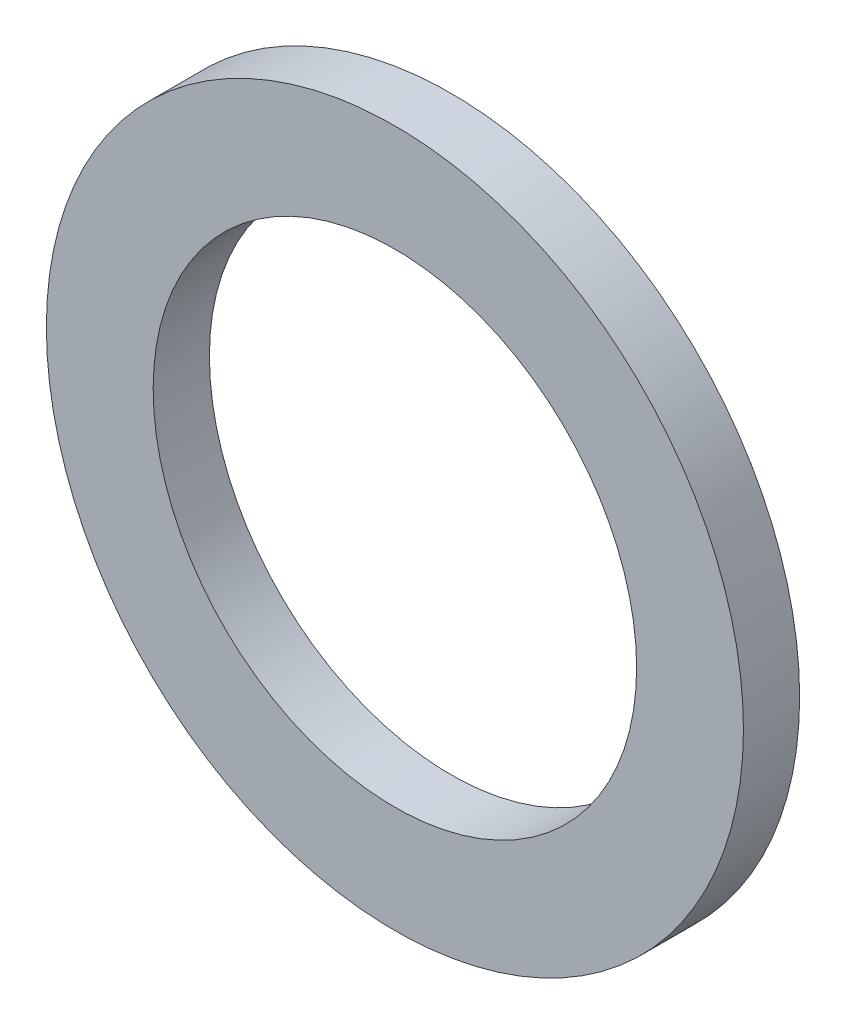
SolidWorks part; units mm, degrees
material "AISI 304"
ref_plane "Спереди" through (0, 0, 0) normal (0, 0, 1) x (1, 0, 0)
ref_plane "Сверху" through (0, 0, 0) normal (0, 1, 0) x (1, 0, 0)
ref_plane "Справа" through (0, 0, 0) normal (1, 0, 0) x (0, 0, -1)
other "Configuration Table"
sketch "Эскиз1" plane through (0, 0, 0) normal (0, 0, 1) x (1, 0, 0)
  circle A0 centre (0, 0) radius 21.5
  circle A1 centre (0, 0) radius 31
  dimension "D1" = 43
  dimension "D2" = 62
extrude "Бобышка-Вытянуть1" add sketch "Эскиз1" along normal blind 5
move or copy body "Тело-Переместить/Копировать2" [suppressed] bodies to move or copy 103 parameters "D1"=0, "D2"=0, "D3"=0
move or copy body "Тело-Переместить/Копировать1" [suppressed] bodies to move or copy 103 parameters "D1"=0, "D2"=0, "D3"=0
